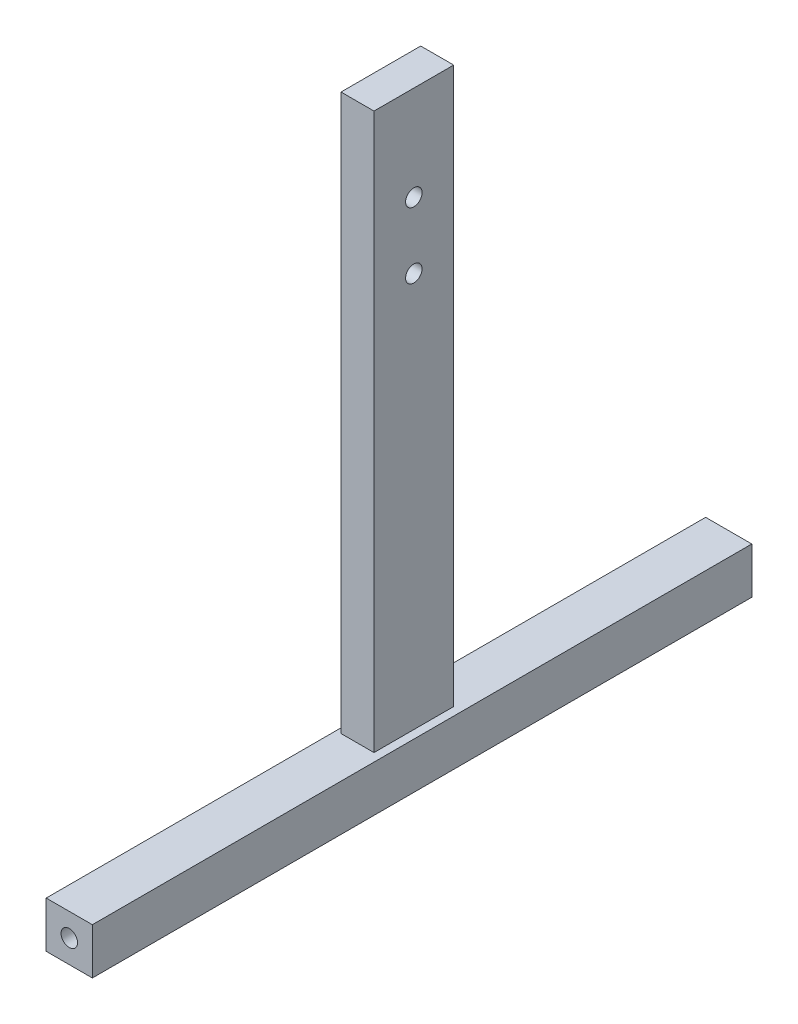
SolidWorks part; units mm, degrees
material "Plain Carbon Steel"
ref_plane "Front Plane" through (0, 0, 0) normal (0, 0, 1) x (1, 0, 0)
ref_plane "Top Plane" through (0, 0, 0) normal (0, 1, 0) x (1, 0, 0)
ref_plane "Right Plane" through (0, 0, 0) normal (1, 0, 0) x (0, 0, -1)
sketch "Sketch1" plane through (0, 0, 0) normal (0, 0, 1) x (1, 0, 0)
  line L1 (-17.78, 17.78) -> (17.78, 17.78)
  line L2 (-17.78, 17.78) -> (-17.78, -17.78)
  line L3 (-17.78, -17.78) -> (17.78, -17.78)
  line L4 (17.78, 17.78) -> (17.78, -17.78)
  line L5 (-17.78, 17.78) -> (17.78, -17.78) construction
  line L6 (-17.78, -17.78) -> (17.78, 17.78) construction
  point P0 (0, 0)
  dimension "D1" = 35.56
  dimension "D2" = 35.56
extrude "Boss-Extrude1" add sketch "Sketch1" along normal blind 508
sketch "Sketch2" plane through (0, 0, 508) normal (0, 0, 1) x (1, 0, 0)
  circle A0 centre (0, 0) radius 6.35
  dimension "D1" = 12.7
extrude "Cut-Extrude1" cut sketch "Sketch2" against normal through all
sketch "Sketch3" plane through (0, 17.78, 0) normal (0, 1, 0) x (1, 0, 0)
  line L0 (17.78, -508) -> (17.78, 0) construction
  line L1 (-13.97, -284.6973) -> (11.43, -284.6973)
  line L2 (-13.97, -284.6973) -> (-13.97, -223.3027)
  line L3 (-13.97, -223.3027) -> (11.43, -223.3027)
  line L4 (11.43, -284.6973) -> (11.43, -223.3027)
  line L5 (-13.97, -284.6973) -> (11.43, -223.3027) construction
  line L6 (-13.97, -223.3027) -> (11.43, -284.6973) construction
  line L7 (17.78, -508) -> (-17.78, -508) construction
  point P0 (-1.27, -254)
  dimension "D1" = 25.4
  dimension "D2" = 6.35
  dimension "D3" = 223.3027
extrude "Boss-Extrude2" add sketch "Sketch3" along normal blind 427.99 separate body
sketch "Sketch4" plane through (-13.97, 0, 0) normal (-1, 0, 0) x (0, 0, 1)
  circle A0 centre (254, 372.872) radius 6.35
  circle A1 centre (254, 322.072) radius 6.35
extrude "Cut-Extrude2" cut sketch "Sketch4" against normal through all
